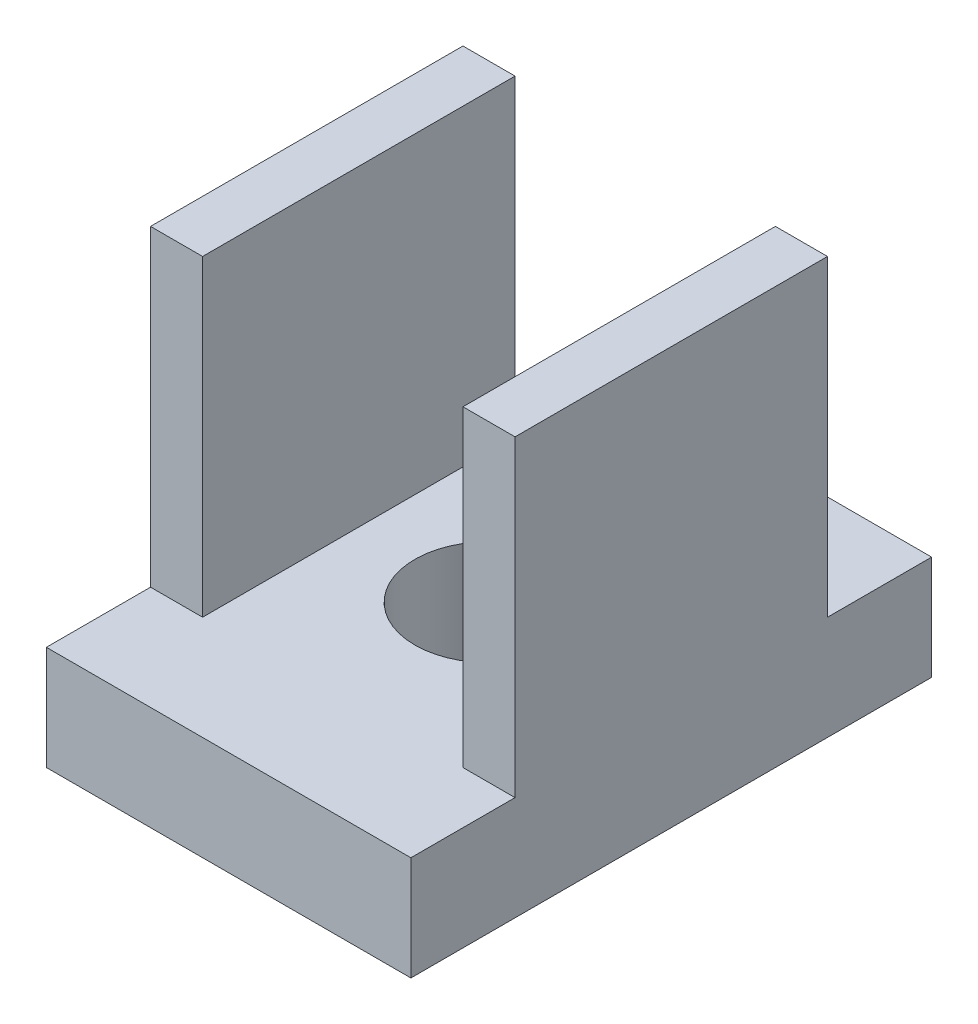
SolidWorks part; units mm, degrees
ref_plane "Front Plane" through (0, 0, 0) normal (0, 0, 1) x (1, 0, 0)
ref_plane "Top Plane" through (0, 0, 0) normal (0, 1, 0) x (1, 0, 0)
ref_plane "Right Plane" through (0, 0, 0) normal (1, 0, 0) x (0, 0, -1)
sketch "Sketch1" plane through (0, 0, 0) normal (0, 1, 0) x (1, 0, 0)
  line L1 (-3.5, 5) -> (3.5, 5)
  line L2 (-3.5, 5) -> (-3.5, -5)
  line L3 (-3.5, -5) -> (3.5, -5)
  line L4 (3.5, 5) -> (3.5, -5)
  line L5 (-3.5, 5) -> (3.5, -5) construction
  line L6 (-3.5, -5) -> (3.5, 5) construction
  point P0 (0, 0)
  dimension "D1" = 7
  dimension "D2" = 10
extrude "Boss-Extrude1" add sketch "Sketch1" along normal blind 2
sketch "Sketch2" plane through (0, 2, 0) normal (0, 1, 0) x (1, 0, 0)
  circle A0 centre (0, 0) radius 1.425
  dimension "D1" = 2.85
extrude "Cut-Extrude1" cut sketch "Sketch2" against normal through all
sketch "Sketch3" plane through (0, 2, 0) normal (0, 1, 0) x (1, 0, 0)
  line L0 (-3.5, 0) -> (3.5, 0) construction
  line L1 (-3.5, 5) -> (-3.5, -5) construction
  line L2 (3.5, -5) -> (3.5, 5) construction
  line L3 (0, -5) -> (0, 5) construction
  line L4 (2.5, -3) -> (3.5, -3)
  line L5 (2.5, -3) -> (2.5, 3)
  line L6 (2.5, 3) -> (3.5, 3)
  line L7 (3.5, -3) -> (3.5, 3)
  line L8 (-3.5, -5) -> (3.5, -5) construction
  line L9 (3.5, 5) -> (-3.5, 5) construction
  line L10 (-3.5, -3) -> (-3.5, 3)
  line L11 (-2.5, 3) -> (-3.5, 3)
  line L12 (-2.5, -3) -> (-2.5, 3)
  line L13 (-2.5, -3) -> (-3.5, -3)
  dimension "D1" = 1
  dimension "D2" = 6
extrude "Boss-Extrude2" add sketch "Sketch3" along normal blind 6
